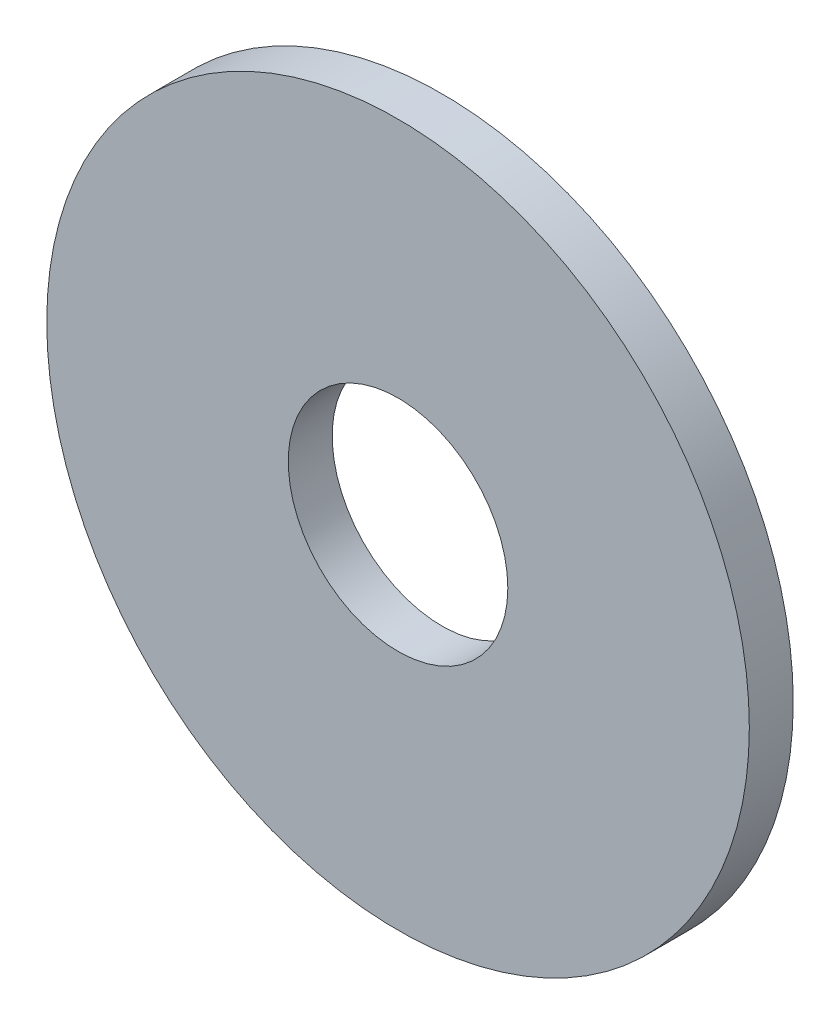
SolidWorks part; units mm, degrees
ref_plane "Front Plane" through (0, 0, 0) normal (0, 0, 1) x (1, 0, 0)
ref_plane "Top Plane" through (0, 0, 0) normal (0, 1, 0) x (1, 0, 0)
ref_plane "Right Plane" through (0, 0, 0) normal (1, 0, 0) x (0, 0, -1)
sketch "Sketch1" plane through (0, 0, 0) normal (0, 0, 1) x (1, 0, 0)
  circle A0 centre (0, 0) radius 16
  circle A1 centre (0, 0) radius 5
  dimension "D1" = 10
  dimension "D2" = 32
extrude "Boss-Extrude1" add sketch "Sketch1" along normal blind 2
